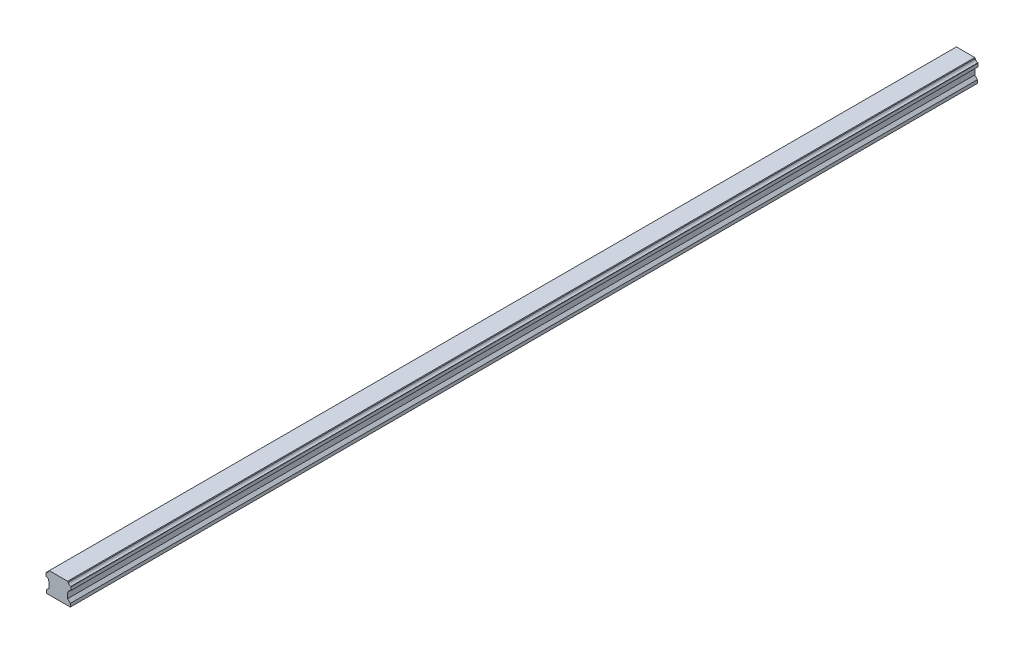
SolidWorks part; units mm, degrees
ref_plane "Piano frontale" through (0, 0, 0) normal (0, 0, 1) x (1, 0, 0)
ref_plane "Piano superiore" through (0, 0, 0) normal (0, 1, 0) x (1, 0, 0)
ref_plane "Piano destro" through (0, 0, 0) normal (1, 0, 0) x (0, 0, -1)
sketch "Schizzo1" plane through (0, 0, 0) normal (0, 0, 1) x (1, 0, 0)
  line L0 (-4.7672, -7.7583) -> (-3.5756, -6.5667)
  line L1 (-3.5756, -6.5667) -> (-3.5756, -4.1833)
  line L2 (-3.5756, -4.1833) -> (-3.8175, -3.9414)
  line L3 (-4.9128, -2.8461) -> (-5.0056, -2.7533)
  line L4 (-5.0056, -2.7533) -> (-5.0056, -1.3233)
  line L5 (-5.0056, -1.3233) -> (-4.9128, -1.2306)
  line L6 (-3.8175, -0.1353) -> (-3.5756, 0.1067)
  line L7 (-3.5756, 0.1067) -> (4.5278, 0.1067)
  line L8 (4.5278, 0.1067) -> (4.7697, -0.1353)
  line L9 (5.865, -1.2306) -> (5.9578, -1.3233)
  line L10 (5.9578, -1.3233) -> (5.9578, -2.7533)
  line L11 (5.9578, -2.7533) -> (5.865, -2.8461)
  line L12 (4.7697, -3.9414) -> (4.5278, -4.1833)
  line L13 (4.5278, -4.1833) -> (4.5278, -6.5667)
  line L14 (4.5278, -6.5667) -> (5.7194, -7.7583)
  line L17 (-4.7672, -7.7583) -> (-4.7672, -9.1883)
  line L18 (-4.7672, -9.1883) -> (5.7194, -9.1883)
  line L19 (5.7194, -9.1883) -> (5.7194, -7.7583)
  arc A0 (-3.8175, -3.9414) -> (-4.9128, -2.8461) centre (-5.0056, -4.0341) ccw
  arc A1 (-4.9128, -1.2306) -> (-3.8175, -0.1353) centre (-5.0056, -0.0425) ccw
  arc A2 (4.7697, -0.1353) -> (5.865, -1.2306) centre (5.9578, -0.0425) ccw
  arc A3 (5.865, -2.8461) -> (4.7697, -3.9414) centre (5.9578, -4.0341) ccw
  dimension "D1" = 1.43
extrude "Estrusione-Estrusione1" add sketch "Schizzo1" along normal blind 400
